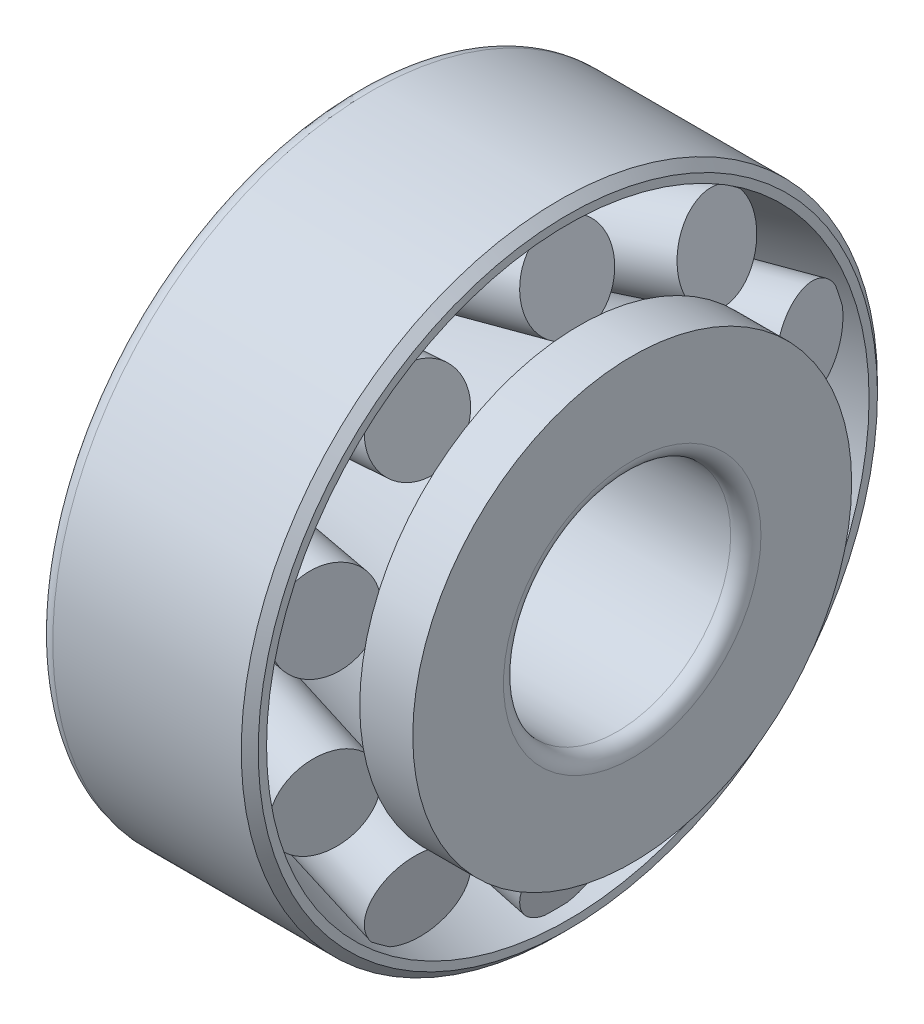
SolidWorks part; units mm, degrees
revolve "OuterRace" add sketch "OutRacSke" angle 360 about L5
sketch "OutRacSke" plane through (0, 0, 0) normal (0, 0, 1) x (1, 0, 0)
  line L0 (-4.25, 19.8873) -> (-18.25, 16.136)
  line L1 (-18.25, 16.136) -> (-18.25, 20)
  line L2 (-17.25, 21) -> (-4.81, 21)
  line L3 (-4.81, 21) -> (-4.25, 20.44)
  line L4 (-4.25, 20.44) -> (-4.25, 19.8873)
  line L5 (-42.5, 0) -> (42.5, 0) construction
  arc A0 (-18.25, 20) -> (-17.25, 21) centre (-17.25, 20) cw
  dimension "cup_radius" = 1
  dimension "OD" = 42
  dimension "cup_width" = 14
  dimension "Tangle" = 15
  dimension "offset" = 18.25
  dimension "chamfer" = 0.56
  dimension "D8" = 45
  dimension "cup_SID" = 32.272
ref_plane "Plane1" through (0, 0, 0) normal (0, 0, 1) x (1, 0, 0)
ref_plane "Plane2" through (0, 0, 0) normal (0, 1, 0) x (1, 0, 0)
ref_plane "Plane3" through (0, 0, 0) normal (1, 0, 0) x (0, 0, -1)
sketch "Clipboard" plane through (0, 0, 0) normal (0, 0, 1) x (1, 0, 0)
  line L0 (0, 0) -> (10, 0) construction
  line L1 (0, 0) -> (31.7817, -5.604)
  line L2 (0, 0) -> (14.7721, 2.6047)
  line L3 (0, 0) -> (41.3619, -7.2932)
  line L4 (0, 0) -> (-12.5981, -0.2199)
  line L5 (0, 0) -> (-6.075, 18.25)
  dimension "Bore" = 15
  dimension "Count" = 10
  dimension "Show_count" = 10
  dimension "Max_count" = 10
  dimension "Min_count" = 1
  dimension "Race_OD" = 42
  dimension "Race_ID" = 32.272
  dimension "cyl_len" = 12.6
  dimension "Roller_diameter" = 6.075
  dimension "OA_width" = 18.25
sketch "RolDetSke" plane through (0, 0, 0) normal (0, 0, 1) x (1, 0, 0)
  line L0 (-16.4638, 13.552) -> (-17.25, 16.486)
  line L1 (-16.4638, 13.552) -> (-4.2932, 16.8131)
  line L2 (-5.0793, 19.7471) -> (-4.2932, 16.8131)
  line L4 (-37.3502, 7.9555) -> (12.5154, 21.3169) construction
  line L5 (-5.0793, 19.7471) -> (-17.25, 16.486)
  line L9 (-4.25, 19.8873) -> (-18.25, 16.136) construction
  dimension "cyl_len" = 12.6
  dimension "Roller_diameter" = 6.075
  dimension "dy" = 16.486
  dimension "D2" = 17.25
revolve "RollerDetailed" add sketch "RolDetSke" angle 360 about L4
sketch "RolSimSke" plane through (0, 0, 0) normal (0, 0, 1) x (1, 0, 0)
  line L0 (0, 0) -> (-32, 0) construction
  line L1 (-17.25, 16.486) -> (-5.0793, 19.7471)
  line L2 (-17.25, 16.486) -> (-15.6777, 10.618)
  line L3 (-15.6777, 10.618) -> (-3.507, 13.8791)
  line L4 (-5.0793, 19.7471) -> (-3.507, 13.8791)
  dimension "Tangle" = 15
  dimension "Roller_diameter" = 6.075
  dimension "dy" = 16.486
  dimension "dx" = 17.25
revolve "RollersSimplified" [suppressed] add sketch "RolSimSke" angle 360 about L0
ref_axis "Axis1" through (-50, 0, 0) along (1, 0, 0)
pattern_circular "RollersDetailed" count 10 every 36 about axis through (-50, 0, 0) along (1, 0, 0) of "RollerDetailed"
sketch "InsRacSke" plane through (0, 0, 0) normal (0, 0, 1) x (1, 0, 0)
  line L0 (-15.7512, 10.9217) -> (-17, 10.9217)
  line L1 (-18.25, 20) -> (-18.25, -20) construction
  line L2 (-17, 10.9217) -> (-17, 8.06)
  line L3 (-17, 8.06) -> (-16.44, 7.5)
  line L4 (-16.44, 7.5) -> (-1, 7.5)
  line L5 (0, 8.5) -> (0, 14.4866)
  line L6 (0, 14.4866) -> (-3.4991, 14.4866)
  line L7 (-3.4991, 14.4866) -> (-3.4991, 13.8791)
  line L8 (-3.4991, 13.8791) -> (-15.6698, 10.618)
  line L9 (-15.6698, 10.618) -> (-15.7512, 10.9217)
  line L10 (-42.5, 0) -> (42.5, 0) construction
  arc A0 (-1, 7.5) -> (0, 8.5) centre (-1, 8.5) ccw
  dimension "Tangle" = 15
  dimension "chamfer" = 0.56
  dimension "Bore" = 15
  dimension "cyl_len" = 12.6
  dimension "dy" = 10.618
  dimension "dx" = 15.6698
  dimension "D11" = 45
  dimension "D2" = 18.25
revolve "InnerRace" add sketch "InsRacSke" angle 360 about L10
sketch "CagSpiSke" plane through (0, 0, 0) normal (0, 0, 1) x (1, 0, 0)
  line L3 (-3.6846, 16.8941) -> (-16.4638, 13.4699)
  line L4 (-16.7502, 12.9739) -> (-16.5406, 12.1915)
  line L6 (-42.5, 0) -> (42.5, 0) construction
  arc A1 (-16.4638, 13.4699) -> (-16.7502, 12.9739) centre (-16.359, 13.0787) ccw
  dimension "Tangle" = 15
  dimension "radius" = 0.405
  dimension "dx" = 16.4638
  dimension "dy" = 13.4699
  dimension "offset" = 1.215
revolve "CageSpine" [suppressed] add sketch "CagSpiSke" angle 0.001 about L6
equation "\"OD@OutRacSke\" = \"Race_OD@Clipboard\""
equation "\"cup_SID@OutRacSke\" = \"Race_ID@Clipboard\""
equation "\"chamfer@OutRacSke\" = \"cup_width@OutRacSke\" / 25"
equation "\"offset@OutRacSke\" = \"OA_width@Clipboard\""
equation "\"D2@RolDetSke\" = \"offset@OutRacSke\" - \"cup_radius@OutRacSke\""
equation "\"dy@RolDetSke\" =  ( ( \"Race_ID@Clipboard\" / 2 ) + ( \"cup_radius@OutRacSke\" ) * tan(\"Tangle@OutRacSke\" * 3.141592654/180) ) * 1.005"
equation "\"cyl_len@RolDetSke\" = \"cyl_len@Clipboard\""
equation "\"Roller_diameter@RolDetSke\" = \"Roller_diameter@Clipboard\""
equation "\"dx@RolSimSke\" = \"offset@OutRacSke\" - \"cup_radius@OutRacSke\""
equation "\"dy@RolSimSke\" =  ( ( \"Race_ID@Clipboard\" / 2 ) + ( \"cup_radius@OutRacSke\" ) * tan(\"Tangle@OutRacSke\" * 3.141592654/180) ) * 1.005"
equation "\"Cyl_Len@RolSimSke\" = \"cyl_len@Clipboard\""
equation "\"Roller_diameter@RolSimSke\" = \"Roller_diameter@Clipboard\""
equation "\"Bore@InsRacSke\" = \"Bore@Clipboard\""
equation "\"Tangle@InsRacSke\" = \"Tangle@OutRacSke\""
equation "\"cyl_len@InsRacSke\" = \"cyl_len@Clipboard\""
equation "\"chamfer@InsRacSke\" = \"chamfer@OutRacSke\""
equation "\"D2@InsRacSke\" = \"OA_width@Clipboard\""
equation "\"dx@InsRacSke\" = \"offset@OutRacSke\" - \"cup_radius@OutRacSke\" -  (  \"Roller_diameter@Clipboard\" * 1.005 )  * sin(\"Tangle@InsRacSke\" * 3.141592654/180)"
equation "\"dy@InsRacSke\" = ( ( \"Race_ID@Clipboard\" / 2 ) + ( \"cup_radius@OutRacSke\" ) * tan(\"Tangle@OutRacSke\" * 3.141592654/180) ) * 1.005 -  ( \"Roller_diameter@Clipboard\" )  * cos(\"Tangle@InsRacSke\" * 3.141592654/180) "
equation "\"front_groove@InsRacSke\" = \"Groove_dp@InsRacSke\" / 2"
equation "\"Tangle@CagSpiSke\" = \"Tangle@OutRacSke\""
equation "\"dx@CagSpiSke\" = ( \"offset@OutRacSke\" - \"cup_radius@OutRacSke\" ) -  (  \"Roller_diameter@Clipboard\" / 2  )  * sin(\"Tangle@InsRacSke\" * 3.141592654/180)"
equation "\"dy@CagSpiSke\" = ( ( \"Race_ID@Clipboard\" / 2 ) + ( \"cup_radius@OutRacSke\" ) * tan(\"Tangle@OutRacSke\" * 3.141592654/180) )  -  ( \"Roller_diameter@Clipboard\" / 2 )  * cos(\"Tangle@InsRacSke\" * 3.141592654/180) "
equation "\"length@CagSpiSke\" = \"cyl_len@Clipboard\" * 1.05"
equation "\"offset@CagSpiSke\" = \"Roller_diameter@Clipboard\" / 5"
equation "\"radius@CagSpiSke\" = \"offset@CagSpiSke\" / 3"
equation "\"D3@CageSpine\" = \"Roller_diameter@Clipboard\" / 6"
equation "\"Max_count@Clipboard\" = int( 3.14159265 / atn(( \"Roller_diameter@Clipboard\" / 2) / sqr( \"dy@CagSpiSke\"  *  \"dy@CagSpiSke\" - ( \"Roller_diameter@Clipboard\" / 2) *  ( \"Roller_diameter@Clipboard\" / 2))))"
equation "\"Max_count@Clipboard\" = ((sgn( \"Max_count@Clipboard\" - \"Count@Clipboard\" )-1)*( \"Max_count@Clipboard\" - \"Count@Clipboard\" ))/-2+ \"Count@Clipboard\""
equation "\"Count@RollersDetailed\" = int( \"Show_count@Clipboard\" ) "
equation "\"Count@RollersDetailed\" = ((sgn( \"Count@RollersDetailed\" - \"Max_count@Clipboard\" )-1)*( \"Count@RollersDetailed\" - \"Max_count@Clipboard\" ))/-2+ \"Max_count@Clipboard\""
equation "\"Count@RollersDetailed\" = ((sgn( \"Count@RollersDetailed\" - \"Min_count@Clipboard\" )+1)*( \"Count@RollersDetailed\" - \"Min_count@Clipboard\"))/2 +\"Min_count@Clipboard\""
equation "\"Angle@RollersDetailed\" = 360.0 / \"Max_count@Clipboard\""
equation "\"Angle@CageSpine\" =  \"Angle@RollersDetailed\" * ( \"Count@RollersDetailed\" -1 + int( \"Count@RollersDetailed\" / \"Max_count@Clipboard\" ) )  + 0.001 -  int( \"Count@RollersDetailed\" / \"Max_count@Clipboard\" ) * 0.001"
equation "\"Angle@CageSpine\" =  \"Angle@CageSpine\" * int( \"Min_count@Clipboard\" / 2) + int(1 / \"Min_count@Clipboard\")  * 0.001"
equation "\"Tangle@RolSimSke\" = \"Tangle@OutRacSke\""
